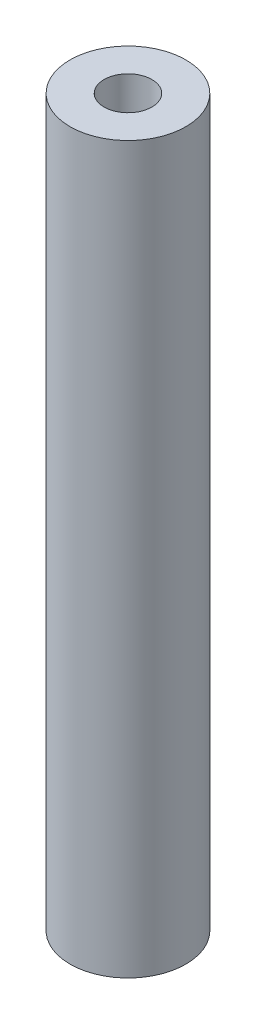
SolidWorks part; units mm, degrees
material "6061 Alloy"
ref_plane "Front Plane" through (0, 0, 0) normal (0, 0, 1) x (1, 0, 0)
ref_plane "Top Plane" through (0, 0, 0) normal (0, 1, 0) x (1, 0, 0)
ref_plane "Right Plane" through (0, 0, 0) normal (1, 0, 0) x (0, 0, -1)
sketch "Sketch1" plane through (0, 0, 0) normal (0, 1, 0) x (1, 0, 0)
  circle A0 centre (0, 0) radius 4
  dimension "D1" = 8
extrude "Boss-Extrude2" add sketch "Sketch1" along normal blind 50.1
sketch "Sketch2" plane through (0, 50.1, 0) normal (0, 1, 0) x (1, 0, 0)
  circle A0 centre (0, 0) radius 1.65
  dimension "D1" = 3.3
extrude "Cut-Extrude1" cut sketch "Sketch2" against normal blind 8
sketch "Sketch3" plane through (0, 0, 0) normal (0, -1, 0) x (1, 0, 0)
  circle A0 centre (0, 0) radius 1.65
  dimension "D1" = 3.3
extrude "Cut-Extrude2" cut sketch "Sketch3" against normal blind 8
equation "\"____ GENERATED PART EXPORTS ____\" = 0"
equation "\"SYS_VersionTag\" = 2"
equation "\"CTRL_MainTowerOD\" = 8mm"
equation "\"STD_DeckStandoffLength\" = 50.1mm"
equation "\"D1@Sketch1\"=\"CTRL_MainTowerOD\""
equation "\"D1@Boss-Extrude2\"=\"STD_DeckStandoffLength\""
equation "\"D1@Sketch2\"=3.3"
equation "\"D1@Sketch3\"=3.3"
